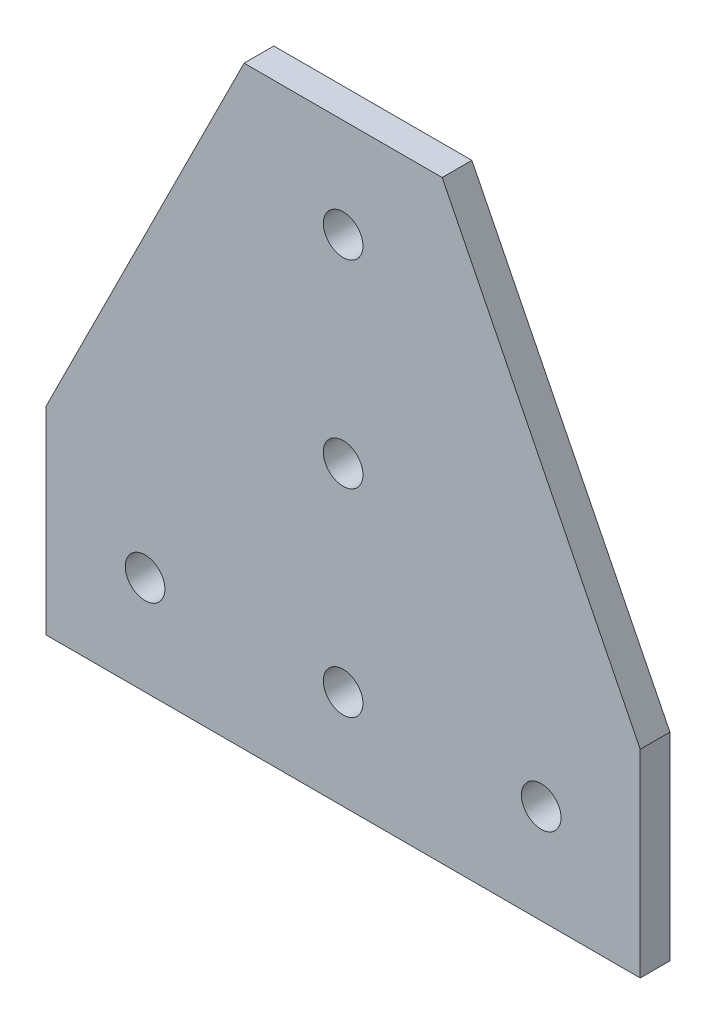
SolidWorks part; units mm, degrees
ref_plane "前视基准面" through (0, 0, 0) normal (0, 0, 1) x (1, 0, 0)
ref_plane "上视基准面" through (0, 0, 0) normal (0, 1, 0) x (1, 0, 0)
ref_plane "右视基准面" through (0, 0, 0) normal (1, 0, 0) x (0, 0, -1)
sketch "草图1" plane through (0, 0, 0) normal (0, 0, 1) x (1, 0, 0)
  line L0 (-64.3558, -40.7419) -> (-4.3558, -40.7419)
  line L1 (-4.3558, -40.7419) -> (-4.3558, -20.7419)
  line L2 (-4.3558, -20.7419) -> (-24.3558, 19.2581)
  line L3 (-24.3558, 19.2581) -> (-44.3558, 19.2581)
  line L4 (-44.3558, 19.2581) -> (-64.3558, -20.7419)
  line L5 (-64.3558, -20.7419) -> (-64.3558, -40.7419)
  circle A0 centre (-54.3558, -30.7419) radius 2
  circle A1 centre (-34.3558, -30.7419) radius 2
  circle A2 centre (-14.3558, -30.7419) radius 2
  circle A3 centre (-34.3558, -10.7419) radius 2
  circle A4 centre (-34.3558, 9.2581) radius 2
  dimension "D1" = 4
extrude "凸台-拉伸1" add sketch "草图1" along normal blind 3
